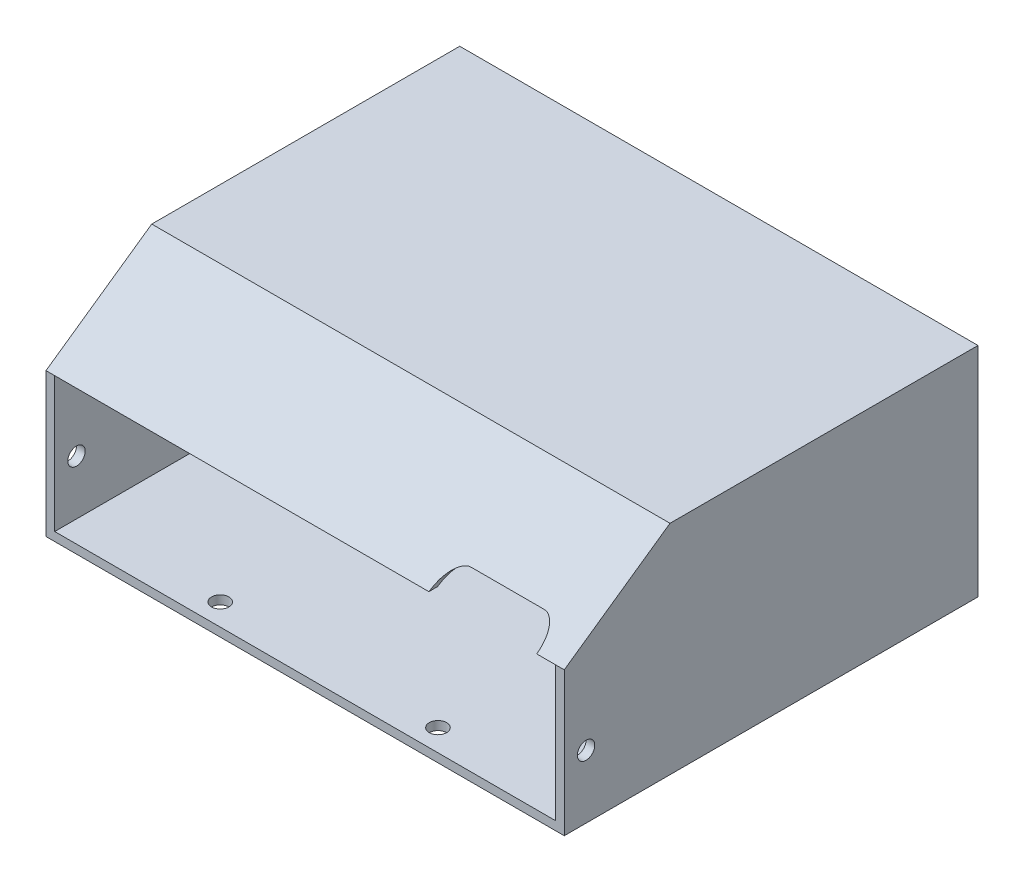
SolidWorks part; units mm, degrees
ref_plane "Front Plane" through (0, 0, 0) normal (0, 0, 1) x (1, 0, 0)
ref_plane "Top Plane" through (0, 0, 0) normal (0, 1, 0) x (1, 0, 0)
ref_plane "Right Plane" through (0, 0, 0) normal (1, 0, 0) x (0, 0, -1)
sketch "Sketch1" plane through (0, 0, 0) normal (0, 0, 1) x (1, 0, 0)
  line L1 (0, 0) -> (119, 0)
  line L2 (0, 0) -> (0, 50)
  line L3 (0, 50) -> (119, 50)
  line L4 (119, 0) -> (119, 50)
  line L5 (0, 0) -> (119, 50) construction
  line L6 (0, 50) -> (119, 0) construction
  point P4 (59.5, 25)
  dimension "D1" = 119
  dimension "D2" = 50
extrude "Boss-Extrude1" add sketch "Sketch1" along normal blind 95
sketch "Sketch2" plane through (0, 0, 95) normal (0, 0, 1) x (1, 0, 0)
  line L0 (119, 50) -> (0, 50) construction
  line L1 (2, 48) -> (117, 48)
  line L2 (2, 48) -> (2, 2)
  line L3 (2, 2) -> (117, 2)
  line L4 (117, 48) -> (117, 2)
  line L5 (2, 48) -> (117, 2) construction
  line L6 (2, 2) -> (117, 48) construction
  line L7 (0, 50) -> (0, 0) construction
  line L8 (119, 0) -> (119, 50) construction
  line L9 (0, 0) -> (119, 0) construction
  point P4 (59.5, 25)
  dimension "D1" = 2
  dimension "D2" = 2
  dimension "D3" = 2
  dimension "D4" = 2
extrude "Cut-Extrude1" cut sketch "Sketch2" against normal offset from surface (92 mm away) 3 up to face at (59.5, 25, 0)
sketch "Sketch3" plane through (0, 0, 3) normal (0, 0, 1) x (1, 0, 0)
  line L0 (2, 25) -> (117, 25) construction
  line L1 (8, 39.5) -> (58, 39.5)
  line L2 (8, 39.5) -> (8, 10.5)
  line L3 (8, 10.5) -> (58, 10.5)
  line L4 (58, 39.5) -> (58, 10.5)
  line L5 (8, 39.5) -> (58, 10.5) construction
  line L6 (8, 10.5) -> (58, 39.5) construction
  line L7 (2, 48) -> (2, 2) construction
  line L8 (117, 2) -> (117, 48) construction
  point P4 (33, 25)
  dimension "D1" = 50
  dimension "D2" = 29
  dimension "D3" = 8
extrude "Cut-Extrude2" cut sketch "Sketch3" against normal blind 10
sketch "Sketch4" plane through (0, 0, 0) normal (0, 0, -1) x (-1, 0, 0)
  circle A0 centre (-32.95, 45) radius 1.95
  circle A1 centre (-32.95, 5) radius 1.95
  dimension "D1" = 3.9
  dimension "D2" = 3.9
extrude "Cut-Extrude3" cut sketch "Sketch4" against normal blind 10
sketch "Sketch5" plane through (0, 0, 3) normal (0, 0, 1) x (1, 0, 0)
  circle A0 centre (32.95, 45) radius 3.25
  circle A1 centre (32.95, 45) radius 1.95
  circle A2 centre (32.95, 5) radius 3.25
  circle A3 centre (32.95, 5) radius 1.95
  dimension "D1" = 6.5
  dimension "D2" = 6.5
extrude "Boss-Extrude3" add sketch "Sketch5" along normal blind 10
fillet "Fillet1" radius 2 2 edges at (32.95, 8.25, 3) (32.95, 41.75, 3)
sketch "Sketch6" plane through (0, 2, 0) normal (0, 1, 0) x (1, 0, 0)
  line L0 (0, -95) -> (119, -95) construction
  circle A0 centre (85, -90) radius 2
  circle A1 centre (35, -90) radius 2
  dimension "D1" = 5
  dimension "D2" = 5
extrude "Cut-Extrude4" cut sketch "Sketch6" against normal blind 10
sketch "Sketch8" plane through (2, 0, 0) normal (1, 0, 0) x (0, 0, -1)
  line L0 (-95, 50) -> (-95, 0) construction
  circle A0 centre (-90, 14.5) radius 2
  dimension "D1" = 5
extrude "Cut-Extrude5" cut sketch "Sketch8" against normal through all both and the other way through all
sketch "Sketch9" plane through (2, 0, 0) normal (1, 0, 0) x (0, 0, -1)
  line L0 (-95, 33) -> (-73.5778, 48)
  line L1 (-3, 48) -> (-95, 48) construction
  line L2 (-73.5778, 48) -> (-71.5778, 48)
  line L3 (-95, 33) -> (-93, 33)
  line L4 (-93, 33) -> (-71.5778, 48)
  line L5 (-95, 0) -> (-95, 50) construction
  point P4 (0, 0)
  point P5 (-72.4449, 48)
  point P8 (-95.0835, 32.8872)
  point P9 (-94, 33)
  point P10 (-95, 33)
  point P13 (-73.8407, 48)
  dimension "D1" = 2
  dimension "D2" = 2
  dimension "D3" = 15
  dimension "D4" = 35
extrude "Boss-Extrude4" add sketch "Sketch9" along normal up to surface (115 mm away) up to face at (117, 14.5, 88)
sketch "Sketch10" plane through (2, 0, 0) normal (1, 0, 0) x (0, 0, -1)
  line L1 (-95, 48) -> (-95, 33) construction
  line L2 (-95, 33) -> (-95, 50)
  line L3 (-95, 50) -> (-70.7215, 50)
  line L4 (-95, 50) -> (0, 50) construction
  line L5 (-70.7215, 50) -> (-95, 33)
  line L6 (-73.5778, 48) -> (-95, 33) construction
  point P0 (-71.9151, 50)
  point P4 (0, 0)
  point P9 (-81.6912, 50)
  point P10 (-87.3872, 34.3521)
  point P11 (0, 0)
  point P12 (-95, 34.1933)
extrude "Cut-Extrude6" cut sketch "Sketch10" against normal through all both and the other way through all
sketch "Sketch11" plane through (0, 0, 0) normal (0, 0, -1) x (-1, 0, 0)
  line L0 (-111, 45) -> (-111, 5) construction
  line L1 (-109.2028, 45) -> (-109.2028, 5)
  line L2 (-112.7972, 45) -> (-112.7972, 5)
  line L3 (-119, 50) -> (0, 50) construction
  line L4 (0, 0) -> (-119, 0) construction
  line L5 (-119, 0) -> (-119, 50) construction
  line L6 (-104, 45) -> (-104, 5) construction
  line L7 (-102.2028, 45) -> (-102.2028, 5)
  line L8 (-105.7972, 45) -> (-105.7972, 5)
  line L9 (-97, 45) -> (-97, 5) construction
  line L10 (-95.2028, 45) -> (-95.2028, 5)
  line L11 (-98.7972, 45) -> (-98.7972, 5)
  line L12 (-90, 45) -> (-90, 5) construction
  line L13 (-88.2028, 45) -> (-88.2028, 5)
  line L14 (-91.7972, 45) -> (-91.7972, 5)
  line L15 (-83, 45) -> (-83, 5) construction
  line L16 (-81.2028, 45) -> (-81.2028, 5)
  line L17 (-84.7972, 45) -> (-84.7972, 5)
  line L18 (-76, 45) -> (-76, 5) construction
  line L19 (-74.2028, 45) -> (-74.2028, 5)
  line L20 (-77.7972, 45) -> (-77.7972, 5)
  line L21 (-69, 45) -> (-69, 5) construction
  line L22 (-67.2028, 45) -> (-67.2028, 5)
  line L23 (-70.7972, 45) -> (-70.7972, 5)
  arc A0 (-109.2028, 45) -> (-112.7972, 45) centre (-111, 45) ccw
  arc A1 (-112.7972, 5) -> (-109.2028, 5) centre (-111, 5) ccw
  arc A2 (-102.2028, 45) -> (-105.7972, 45) centre (-104, 45) ccw
  arc A3 (-105.7972, 5) -> (-102.2028, 5) centre (-104, 5) ccw
  arc A4 (-95.2028, 45) -> (-98.7972, 45) centre (-97, 45) ccw
  arc A5 (-98.7972, 5) -> (-95.2028, 5) centre (-97, 5) ccw
  arc A6 (-88.2028, 45) -> (-91.7972, 45) centre (-90, 45) ccw
  arc A7 (-91.7972, 5) -> (-88.2028, 5) centre (-90, 5) ccw
  arc A8 (-81.2028, 45) -> (-84.7972, 45) centre (-83, 45) ccw
  arc A9 (-84.7972, 5) -> (-81.2028, 5) centre (-83, 5) ccw
  arc A10 (-74.2028, 45) -> (-77.7972, 45) centre (-76, 45) ccw
  arc A11 (-77.7972, 5) -> (-74.2028, 5) centre (-76, 5) ccw
  arc A12 (-67.2028, 45) -> (-70.7972, 45) centre (-69, 45) ccw
  arc A13 (-70.7972, 5) -> (-67.2028, 5) centre (-69, 5) ccw
  point P2 (-111, 25)
  point P16 (-104, 25)
  point P23 (-97, 25)
  point P30 (-90, 25)
  point P37 (-83, 25)
  point P44 (-76, 25)
  point P51 (-69, 25)
  dimension "D1" = 5
  dimension "D2" = 5
  dimension "D3" = 8
  dimension "D4" = 7
extrude "Cut-Extrude8" cut sketch "Sketch11" against normal blind 10
ref_plane "Plane1" through (0, 0, 10) normal (0, 0, 1) x (1, 0, 0)
sketch "Sketch12" plane through (0, 0, 10) normal (0, 0, 1) x (1, 0, 0)
  line L0 (108.6674, 33) -> (91.9107, 33) construction
  line L1 (117, 33) -> (2, 33) construction
  line L2 (108.6674, 29) -> (91.9107, 29)
  line L3 (108.6674, 37) -> (91.9107, 37)
  arc A0 (108.6674, 29) -> (108.6674, 37) centre (108.6674, 33) ccw
  arc A1 (91.9107, 37) -> (91.9107, 29) centre (91.9107, 33) ccw
  point P4 (100.2891, 33)
  dimension "D1" = 4
extrude "Cut-Extrude9" cut sketch "Sketch12" along normal through all
